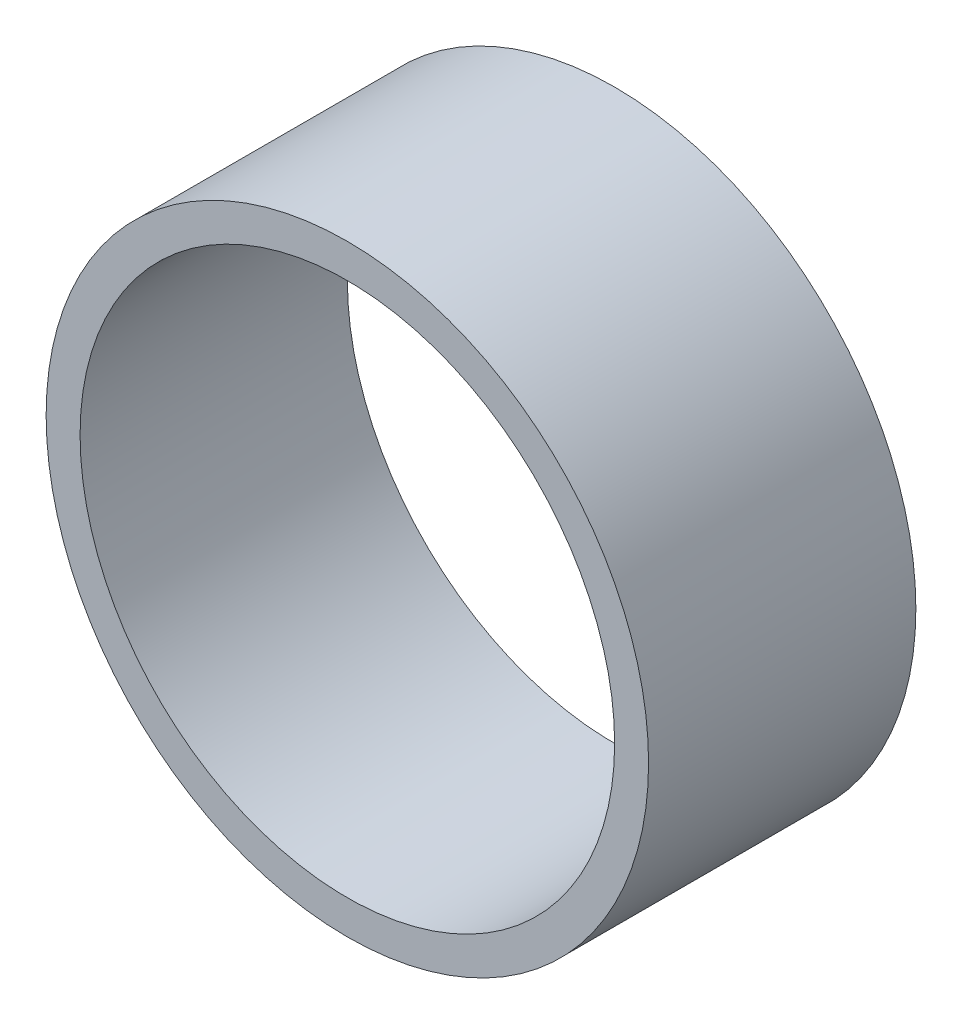
SolidWorks part; units mm, degrees
ref_plane "Front Plane" through (0, 0, 0) normal (0, 0, 1) x (1, 0, 0)
ref_plane "Top Plane" through (0, 0, 0) normal (0, 1, 0) x (1, 0, 0)
ref_plane "Right Plane" through (0, 0, 0) normal (1, 0, 0) x (0, 0, -1)
sketch "Sketch1" plane through (0, 0, 0) normal (0, 0, 1) x (1, 0, 0)
  circle A0 centre (0, 0) radius 14.3129
  circle A1 centre (0, 0) radius 12.7
  dimension "D1" = 28.6258
  dimension "ID" = 25.4
extrude "Extrude1" add sketch "Sketch1" along normal mid plane 12.7
sketch "Sketch2" plane through (0, 0, 0) normal (1, 0, 0) x (0, 0, -1)
  line L0 (-6.35, -12.7) -> (6.35, -12.7) construction
  line L3 (6.35, 12.7) -> (-6.35, 12.7) construction
  line L5 (-6.35, -12.7) -> (6.35, -12.7)
  line L6 (6.35, 12.7) -> (-6.35, 12.7)
sketch "Sketch4" plane through (0, 0, 6.35) normal (0, 0, 1) x (1, 0, 0)
  line L0 (0, 0) -> (-8.9803, 8.9803)
  line L1 (0, -3.4925) -> (0, 3.4925) construction
  circle A0 centre (0, 0) radius 12.7 construction
  dimension "D1" = 45
